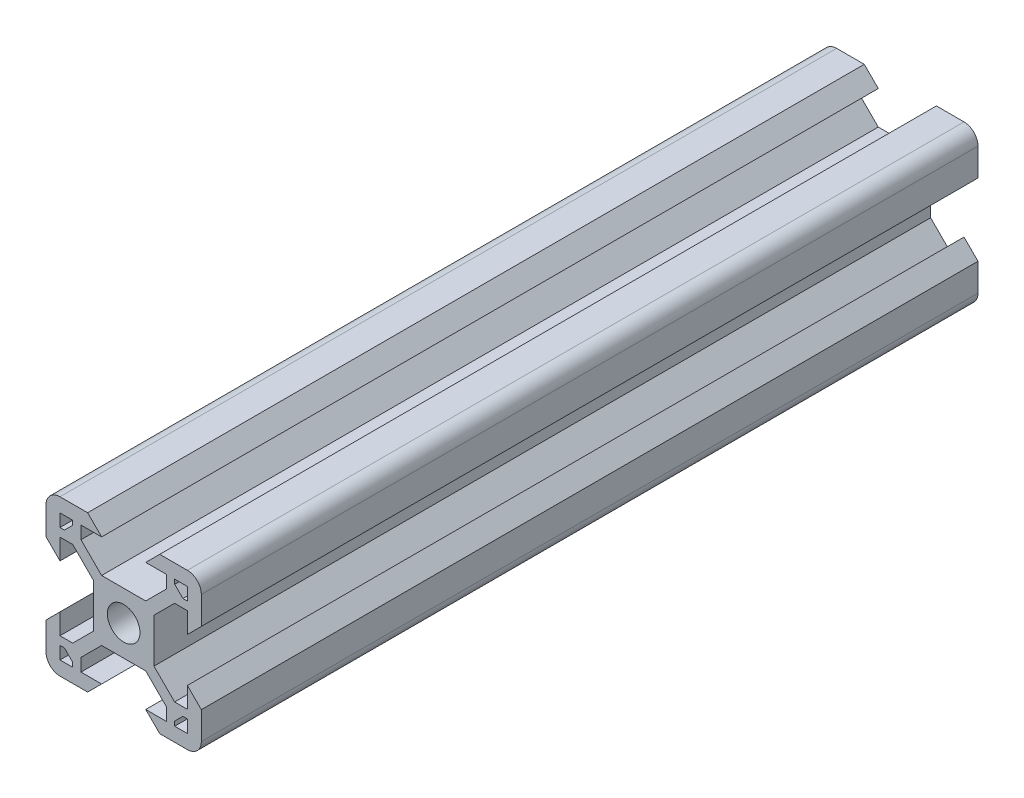
SolidWorks part; units mm, degrees
material "5052-H38, Barre (SS)"
ref_plane "Plan de face" through (0, 0, 0) normal (0, 0, 1) x (1, 0, 0)
ref_plane "Plan de dessus" through (0, 0, 0) normal (0, 1, 0) x (1, 0, 0)
ref_plane "Plan de droite" through (0, 0, 0) normal (1, 0, 0) x (0, 0, -1)
sketch "Esquisse1" plane through (0, 0, 0) normal (0, 0, 1) x (1, 0, 0)
  line L0 (-3.9007, 0) -> (-3.9007, -2.84)
  line L1 (-3.9007, -2.84) -> (-6.56, -5.4993)
  line L2 (-6.56, -5.4993) -> (-8.2, -5.4993)
  line L3 (-8.2, -5.4993) -> (-8.2, -2.84)
  line L4 (-8.2, -2.84) -> (-10, -4.64)
  line L5 (-10, -4.64) -> (-10, -8.2)
  line L6 (0, 0) -> (-17.0509, -17.0509) construction
  line L7 (0, 0) -> (0, -17.0509) construction
  line L8 (0, 0) -> (-30.3777, 0) construction
  line L9 (-4.64, -10) -> (-8.2, -10)
  line L10 (-2.84, -8.2) -> (-4.64, -10)
  line L11 (-5.4993, -8.2) -> (-2.84, -8.2)
  line L12 (-5.4993, -6.56) -> (-5.4993, -8.2)
  line L13 (-2.84, -3.9007) -> (-5.4993, -6.56)
  line L14 (0, -3.9007) -> (-2.84, -3.9007)
  line L15 (-8.2, -8.2) -> (-8.2, -6.5693)
  line L16 (-8.2, -6.5693) -> (-7.63, -6.5693)
  line L17 (-7.63, -6.5693) -> (-6.5693, -7.63)
  line L18 (-6.5693, -7.63) -> (-6.5693, -8.2)
  line L19 (-6.5693, -8.2) -> (-8.2, -8.2)
  line L20 (-3.9007, 0) -> (-3.9007, 2.84)
  line L21 (-3.9007, 2.84) -> (-6.56, 5.4993)
  line L22 (-6.56, 5.4993) -> (-8.2, 5.4993)
  line L23 (-8.2, 5.4993) -> (-8.2, 2.84)
  line L24 (-8.2, 2.84) -> (-10, 4.64)
  line L25 (-10, 4.64) -> (-10, 8.2)
  line L26 (-4.64, 10) -> (-8.2, 10)
  line L27 (-2.84, 8.2) -> (-4.64, 10)
  line L28 (-5.4993, 8.2) -> (-2.84, 8.2)
  line L29 (-5.4993, 6.56) -> (-5.4993, 8.2)
  line L30 (-2.84, 3.9007) -> (-5.4993, 6.56)
  line L31 (0, 3.9007) -> (-2.84, 3.9007)
  line L32 (-8.2, 6.5693) -> (-8.2, 8.2)
  line L33 (-8.2, 8.2) -> (-6.5693, 8.2)
  line L34 (-6.5693, 8.2) -> (-6.5693, 7.63)
  line L35 (-6.5693, 7.63) -> (-7.63, 6.5693)
  line L36 (-7.63, 6.5693) -> (-8.2, 6.5693)
  line L37 (0, 3.9007) -> (2.84, 3.9007)
  line L38 (2.84, 3.9007) -> (5.4993, 6.56)
  line L39 (5.4993, 6.56) -> (5.4993, 8.2)
  line L40 (5.4993, 8.2) -> (2.84, 8.2)
  line L41 (2.84, 8.2) -> (4.64, 10)
  line L42 (4.64, 10) -> (8.2, 10)
  line L43 (10, 4.64) -> (10, 8.2)
  line L44 (8.2, 2.84) -> (10, 4.64)
  line L45 (8.2, 5.4993) -> (8.2, 2.84)
  line L46 (6.56, 5.4993) -> (8.2, 5.4993)
  line L47 (3.9007, 2.84) -> (6.56, 5.4993)
  line L48 (3.9007, 0) -> (3.9007, 2.84)
  line L49 (6.5693, 8.2) -> (8.2, 8.2)
  line L50 (8.2, 8.2) -> (8.2, 6.5693)
  line L51 (8.2, 6.5693) -> (7.63, 6.5693)
  line L52 (7.63, 6.5693) -> (6.5693, 7.63)
  line L53 (6.5693, 7.63) -> (6.5693, 8.2)
  line L54 (3.9007, 0) -> (3.9007, -2.84)
  line L55 (3.9007, -2.84) -> (6.56, -5.4993)
  line L56 (6.56, -5.4993) -> (8.2, -5.4993)
  line L57 (8.2, -5.4993) -> (8.2, -2.84)
  line L58 (8.2, -2.84) -> (10, -4.64)
  line L59 (10, -4.64) -> (10, -8.2)
  line L60 (4.64, -10) -> (8.2, -10)
  line L61 (2.84, -8.2) -> (4.64, -10)
  line L62 (5.4993, -8.2) -> (2.84, -8.2)
  line L63 (5.4993, -6.56) -> (5.4993, -8.2)
  line L64 (2.84, -3.9007) -> (5.4993, -6.56)
  line L65 (0, -3.9007) -> (2.84, -3.9007)
  line L66 (8.2, -6.5693) -> (8.2, -8.2)
  line L67 (8.2, -8.2) -> (6.5693, -8.2)
  line L68 (6.5693, -8.2) -> (6.5693, -7.63)
  line L69 (6.5693, -7.63) -> (7.63, -6.5693)
  line L70 (7.63, -6.5693) -> (8.2, -6.5693)
  circle A0 centre (0, 0) radius 2.1
  arc A1 (-10, -8.2) -> (-8.2, -10) centre (-8.2, -8.2) ccw
  arc A2 (-8.2, 10) -> (-10, 8.2) centre (-8.2, 8.2) ccw
  arc A3 (10, 8.2) -> (8.2, 10) centre (8.2, 8.2) ccw
  arc A4 (8.2, -10) -> (10, -8.2) centre (8.2, -8.2) ccw
  point P23 (-7.0997, -7.0997)
  dimension "D4" = 4.2
  dimension "D1" = 45
  dimension "D2" = 5.68
  dimension "D3" = 1.64
  dimension "D5" = 1.5
  dimension "D6" = 20
  dimension "D7" = 1.8
  dimension "D8" = 1.07
  dimension "D9" = 4
extrude "Boss.-Extru.2" add sketch "Esquisse1" along normal mid plane 100
